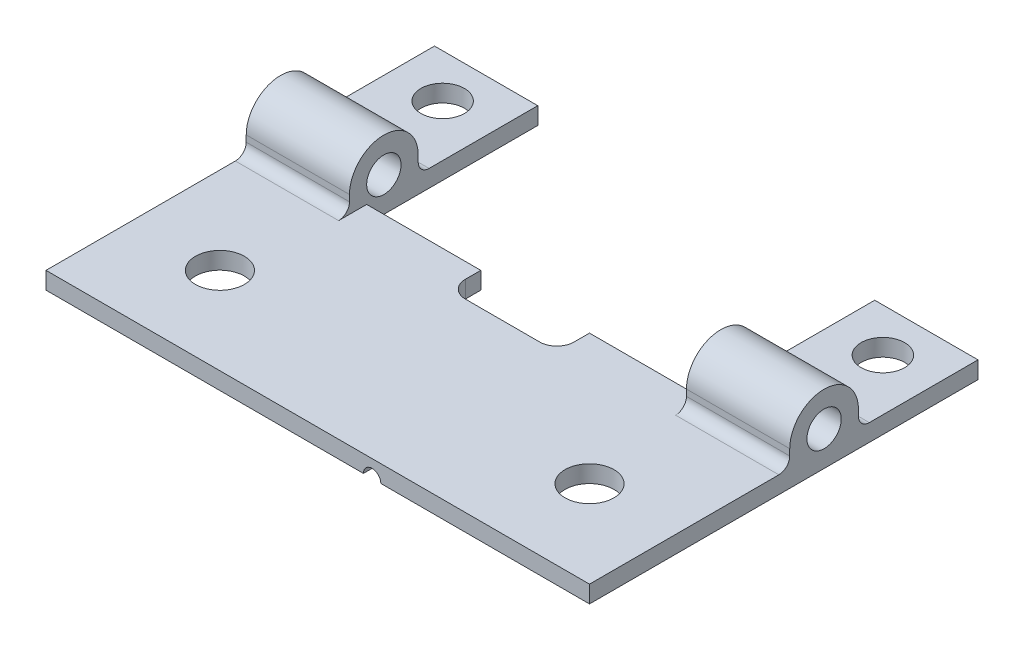
SolidWorks part; units mm, degrees
ref_plane "Front Plane" through (0, 0, 0) normal (0, 0, 1) x (1, 0, 0)
ref_plane "Top Plane" through (0, 0, 0) normal (0, 1, 0) x (1, 0, 0)
ref_plane "Right Plane" through (0, 0, 0) normal (1, 0, 0) x (0, 0, -1)
sketch "Sketch1" plane through (0, 0, 0) normal (0, 1, 0) x (1, 0, 0)
  line L1 (-11.1768, -1.7511) -> (13.8232, -1.7511)
  line L2 (-11.1768, -1.7511) -> (-11.1768, 8.2489)
  line L3 (-11.1768, 8.2489) -> (13.8232, 8.2489)
  line L4 (13.8232, -1.7511) -> (13.8232, 8.2489)
  dimension "D1" = 25
  dimension "D2" = 10
extrude "Base Plate" add sketch "Sketch1" along normal blind 0.79
sketch "Sketch2" plane through (-11.1768, 0, 0) normal (-1, 0, 0) x (0, 0, 1)
  line L0 (-8.2489, 0) -> (-9.0389, 0)
  line L2 (-8.2489, 0.79) -> (-9.0389, 0.79) construction
  line L4 (-8.2489, 0) -> (-8.2489, 0.79)
  line L7 (-7.4589, 0.79) -> (-8.2489, 0.79)
  line L10 (-8.2489, 0.79) -> (-7.4589, 0.79)
  line L12 (-8.2489, 1.58) -> (-8.2489, 0.79) construction
  line L13 (-7.4589, 1.58) -> (-7.4589, 0.79)
  line L14 (-8.2489, 0.79) -> (-7.4589, 0.79)
  line L15 (-10.6189, 1.58) -> (-10.6189, 0) construction
  line L16 (-8.2489, 0) -> (-11.4266, 0)
  line L17 (-8.2489, 0) -> (-8.2489, 0.79)
  line L18 (-8.2489, 0.79) -> (-9.0389, 0.79) construction
  line L20 (-10.6189, 1.58) -> (-10.6189, 1.29)
  line L23 (-11.4266, 0) -> (-16.1189, 0)
  line L24 (-16.1189, 0.79) -> (-16.1189, 0)
  line L25 (-11.1189, 0.79) -> (-16.1189, 0.79)
  arc A4 (-9.0389, 0) -> (-8.2489, 0.79) centre (-9.0389, 0.79) ccw construction
  arc A5 (-8.2489, 1.58) -> (-9.0389, 0.79) centre (-9.0389, 1.58) ccw construction
  arc A6 (-7.4589, 1.58) -> (-10.6189, 1.58) centre (-9.0389, 1.58) ccw
  arc A9 (-11.4089, 0.79) -> (-10.6189, 1.58) centre (-11.4089, 1.58) ccw construction
  arc A10 (-11.1189, 0.79) -> (-10.6189, 1.29) centre (-11.1189, 1.29) ccw
  point P0 (-9.0389, 0)
  point P1 (-8.2489, 0)
  point P6 (-7.4589, 0.79)
  point P9 (-8.2489, 0.79)
  point P10 (-9.0389, 0.79)
  point P12 (-9.0389, 1.58)
  point P16 (-7.4589, 1.58)
  point P18 (-10.4072, 0.79)
  point P19 (-8.2489, 1.58)
  point P21 (-9.0389, 0.79)
  point P22 (-8.2489, 0.79)
  point P23 (-10.6189, 1.58)
  point P26 (-8.2489, 0.79)
  point P31 (-11.4089, 1.58)
  line M20 (1.7511, 0.79) -> (-8.2489, 0.79)
  line M21 (-8.2489, 0.79) -> (-8.2489, 0)
  dimension "D1" = 0.5
  dimension "D2" = 5
extrude "PinHolder" add sketch "Sketch2" against normal blind 4.75 contours L13 A6 L0 M21 M20
sketch "Sketch4" plane through (-11.1768, 0, 0) normal (-1, 0, 0) x (0, 0, 1)
  line L0 (-9.0389, 0.79) -> (-7.4589, 0.79) construction
  circle A0 centre (-9.0389, 1.58) radius 0.79
  circle A2 centre (-7.4589, 0.79) radius 0.79 construction
  circle A3 centre (-8.2489, 0.79) radius 0.79 construction
  circle A4 centre (-9.0389, 0.79) radius 0.79 construction
  point P1 (-9.0389, 1.58)
  point P6 (-9.0389, 0.79)
  point P7 (-7.4589, 0.79)
  point P8 (-8.2489, 0.79)
  point P12 (0, 0)
  dimension "D1" = 1.58
extrude "Pin Shaft" cut sketch "Sketch4" against normal through all
sketch "Sketch5" plane through (0, 0.79, 0) normal (0, 1, 0) x (1, 0, 0)
  line L0 (-11.1768, 7.4589) -> (-11.1768, -1.7511) construction
  line L1 (-11.1768, -1.7511) -> (13.8232, -1.7511) construction
  line L2 (13.8232, -1.7511) -> (13.8232, 8.2489) construction
  circle A0 centre (-7.1768, 2.2489) radius 1.125
  circle A1 centre (9.8232, 2.2489) radius 1.125
  dimension "D5" = 2.25
  dimension "D6" = 2.25
  dimension "D1" = 4
  dimension "D2" = 4
  dimension "D3" = 4
  dimension "D4" = 4
extrude "Screw Holes" cut sketch "Sketch5" against normal blind 4
sketch "Sketch7" plane through (0, 0, 1.7511) normal (0, 0, 1) x (1, 0, 0)
  line L0 (1.3232, 0) -> (1.3232, 0.79) construction
  line L1 (-11.1768, 0.79) -> (13.8232, 0.79)
  line L2 (-11.1768, 0.79) -> (-11.1768, 0)
  line L3 (-11.1768, 0) -> (13.8232, 0)
  line L4 (13.8232, 0.79) -> (13.8232, 0)
sketch "Sketch11" plane through (0, 0.79, 0) normal (0, 1, 0) x (1, 0, 0)
  line L0 (-6.4268, 11.1189) -> (-6.4268, 16.1189) construction
  line L1 (-11.1768, 16.1189) -> (-6.4268, 16.1189) construction
  line L2 (-11.1768, 16.1189) -> (-11.1768, 12.1189) construction
  line L3 (-11.1768, 12.1189) -> (-6.4268, 12.1189) construction
  line L4 (-6.4268, 16.1189) -> (-6.4268, 12.1189) construction
  circle A0 centre (-8.8018, 14.1189) radius 1
  point P0 (-11.1768, 16.1189)
  point P8 (-8.8018, 16.1189)
  point P9 (-6.4268, 14.1189)
  point P14 (-8.8018, 14.1189)
  dimension "D2" = 2
  dimension "D1" = 4
extrude "Set Screw Hole" cut sketch "Sketch11" against normal blind 1.5 contours A0
ref_plane "Plane1" through (1.3232, 0, 0) normal (1, 0, 0) x (0, 0, -1)
fillet "Mirrored Fillets" radius 0.5 1 edges at (-8.8018, 0.79, -7.4589)
mirror "Mirror1" about plane through (1.3232, 0, 0) normal (1, 0, 0) of "Set Screw Hole", "Pin Shaft", "PinHolder", "Mirrored Fillets"
sketch "Sketch8" plane through (0, 0, 0) normal (0, -1, 0) x (1, 0, 0)
  line L0 (9.0732, -8.2489) -> (-6.4268, -8.2489) construction
  line L1 (13.8232, 1.7511) -> (13.8232, -16.1189) construction
  line L2 (3.8232, -8.2489) -> (3.8232, 1.7511)
  line L3 (-11.1768, 1.7511) -> (13.8232, 1.7511) construction
  point P0 (3.8232, -8.2489)
  dimension "D1" = 10
sketch "Sketch9" plane through (0, 0, 1.7511) normal (0, 0, 1) x (1, 0, 0)
  line L2 (13.8232, 0) -> (13.8232, 0.7186)
  ellipse E0 centre (3.8232, 0) end of major axis (4.2232, 0) minor radius 0.4
  point P0 (13.8232, 0)
  point P7 (3.8232, 0)
  dimension "D1" = 10
  dimension "D2" = 0.4
  dimension "D3" = 0.8
sweep "Wire Groove" cut profiles "Sketch9" path "Sketch8"
sketch "Sketch10" plane through (0, 0, -8.2489) normal (0, 0, -1) x (-1, 0, 0)
  line L0 (11.1768, 0.79) -> (-13.8232, 0.79) construction
  line L1 (-3.8232, 0.79) -> (1.1768, 0.79)
  line L2 (-3.8232, 0.79) -> (-3.8232, 0)
  line L3 (-3.8232, 0) -> (1.1768, 0)
  line L4 (1.1768, 0.79) -> (1.1768, 0)
  line L5 (11.1768, 0) -> (-13.8232, 0) construction
  line L6 (-13.8232, 0.79) -> (-13.8232, 0) construction
  dimension "D1" = 10
  dimension "D2" = 5
extrude "Spring Groove" cut sketch "Sketch10" against normal blind 1.5
fillet "Fillet2" radius 0.79 2 edges at (-1.1768, 0.395, -6.7489) (3.8232, 0.595, -6.7489)
